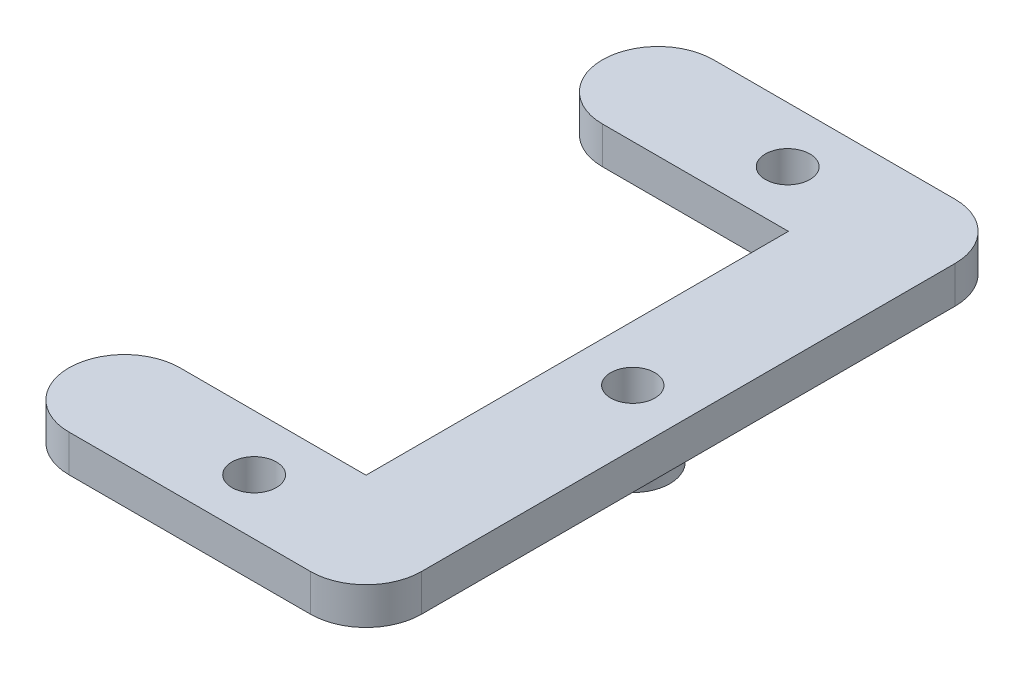
SolidWorks part; units mm, degrees
ref_plane "Front Plane" through (0, 0, 0) normal (0, 0, 1) x (1, 0, 0)
ref_plane "Top Plane" through (0, 0, 0) normal (0, 1, 0) x (1, 0, 0)
ref_plane "Right Plane" through (0, 0, 0) normal (1, 0, 0) x (0, 0, -1)
sketch "Sketch1" plane through (0, 0, 0) normal (0, 1, 0) x (1, 0, 0)
  line L0 (0, -18) -> (0, 18) construction
  line L4 (-8.75, 14.25) -> (3.8, 14.25)
  line L5 (3.8, 14.25) -> (3.8, -14.25)
  line L6 (3.8, -14.25) -> (-8.75, -14.25)
  line L8 (-8.75, -21.75) -> (7.55, -21.75)
  line L9 (11.3, -18) -> (11.3, 18)
  line L10 (7.55, 21.75) -> (-8.75, 21.75)
  circle A0 centre (0, 18) radius 1.5
  circle A1 centre (0, -18) radius 1.5
  arc A6 (11.3, 18) -> (7.55, 21.75) centre (7.55, 18) ccw
  arc A7 (11.3, -18) -> (7.55, -21.75) centre (7.55, -18) cw
  arc A11 (-8.75, 21.75) -> (-8.75, 14.25) centre (-8.75, 18) ccw
  arc A12 (-8.75, -14.25) -> (-8.75, -21.75) centre (-8.75, -18) ccw
  point P2 (0, 0)
  point P10 (0, 0)
  dimension "D1" = 3
  dimension "D3" = 8.75
  dimension "D5" = 3.75
  dimension "D6" = 3.75
  dimension "D8" = 8.75
  dimension "D2" = 36
  dimension "D4" = 7.5
  dimension "D9" = 3.8
extrude "Boss-Extrude1" add sketch "Sketch1" along normal blind 2.5
sketch "Sketch2" plane through (0, 0, 0) normal (0, -1, 0) x (1, 0, 0)
  line L0 (3.8, -14.25) -> (3.8, 14.25) construction
  circle A0 centre (7.55, 0) radius 2.5
  dimension "D1" = 5
  dimension "D2" = 3.75
extrude "Boss-Extrude2" add sketch "Sketch2" along normal blind 2
sketch "Sketch3" plane through (0, -2, 0) normal (0, -1, 0) x (1, 0, 0)
  circle A0 centre (7.55, 0) radius 1.49
  dimension "D1" = 2.98
extrude "Cut-Extrude1" cut sketch "Sketch3" against normal blind 7 contours A0
